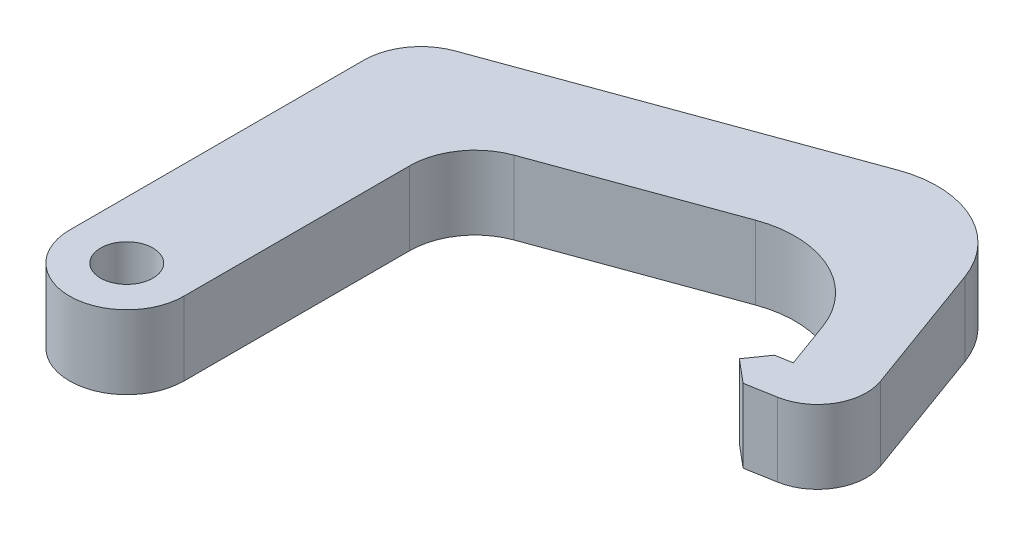
SolidWorks part; units mm, degrees
ref_plane "Front Plane" through (0, 0, 0) normal (0, 0, 1) x (1, 0, 0)
ref_plane "Top Plane" through (0, 0, 0) normal (0, 1, 0) x (1, 0, 0)
ref_plane "Right Plane" through (0, 0, 0) normal (1, 0, 0) x (0, 0, -1)
sketch "Sketch1" plane through (0, 0, 0) normal (0, 1, 0) x (1, 0, 0)
  line L0 (0, 0) -> (0, 18) construction
  line L1 (-3.5, 0) -> (-3.5, 18)
  line L2 (3.5, 0) -> (3.5, 18)
  line L3 (0, 18) -> (25.501, 27.2816) construction
  line L6 (-1.1971, 21.2889) -> (24.3039, 30.5705)
  line L7 (0, 0) -> (22.721, 14.5861) construction
  line L8 (22.5973, 23.5643) -> (25.6755, 15.1071)
  line L9 (24.3039, 30.5705) -> (30.5437, 13.4269)
  line L10 (22.5973, 23.5643) -> (3.1568, 16.4885)
  line L12 (30.5437, 13.4269) -> (25.221, 12.4884)
  line L14 (25.6755, 15.1071) -> (22.721, 14.5861)
  line L15 (25.221, 12.4884) -> (22.721, 14.5861)
  arc A0 (-3.5, 0) -> (3.5, 0) centre (0, 0) ccw
  arc A1 (3.5, 18) -> (-3.5, 18) centre (0, 18) ccw
  circle A4 centre (0, 0) radius 1.6
  point P3 (0, 9)
  dimension "D1" = 3.2
  dimension "D2" = 3.5
  dimension "D3" = 110
  dimension "D4" = 18
  dimension "D5" = 6
  dimension "D6" = 9
  dimension "D7" = 3
  dimension "D8" = 2.5
  dimension "D9" = 2.5
  dimension "D10" = 80
  dimension "D11" = 4
  dimension "D12" = 27
extrude "Boss-Extrude1" add sketch "Sketch1" along normal blind 4.5
fillet "Fillet1" radius 4 1 edges at (3.5, 2.25, -16.6135)
fillet "Fillet2" radius 6 2 edges at (24.3039, 2.25, -30.5705) (22.5973, 2.25, -23.5643)
fillet "Fillet3" radius 3 1 edges at (30.5437, 2.25, -13.4269)
chamfer "Chamfer1" distance 2 angle 45 1 edges at (22.721, 2.25, -14.5861)
